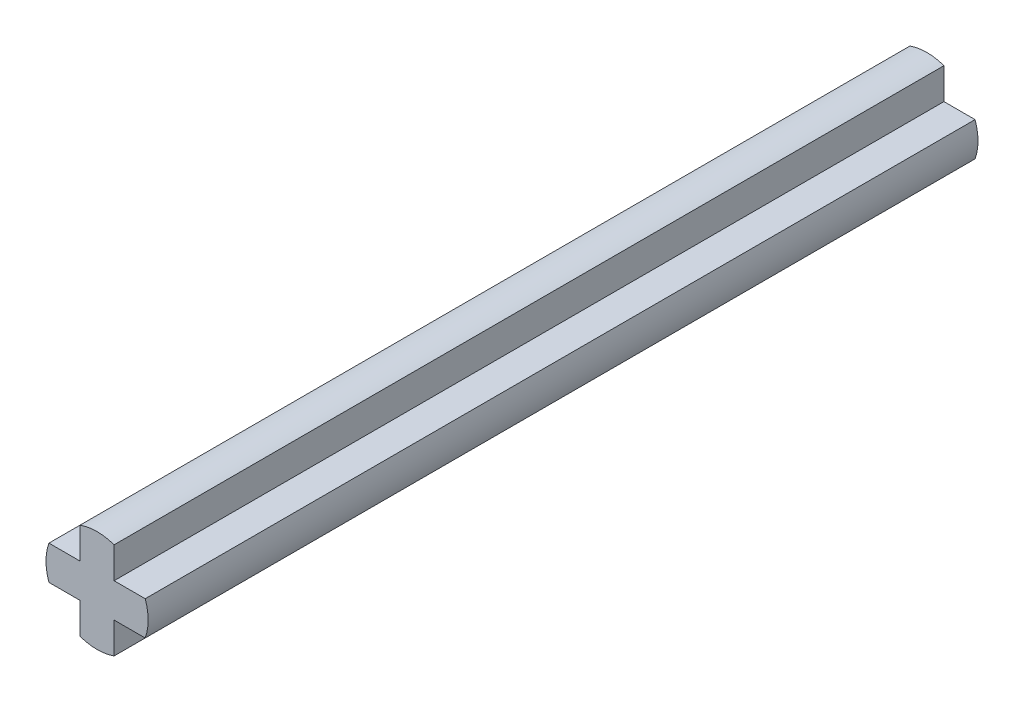
SolidWorks part; units mm, degrees
ref_plane "Plan de face" through (0, 0, 0) normal (0, 0, 1) x (1, 0, 0)
ref_plane "Plan de dessus" through (0, 0, 0) normal (0, 1, 0) x (1, 0, 0)
ref_plane "Plan de droite" through (0, 0, 0) normal (1, 0, 0) x (0, 0, -1)
sketch "Esquisse1" plane through (0, 0, 0) normal (0, 0, 1) x (1, 0, 0)
  line L0 (0.8, 0.8) -> (2.2627, 0.8)
  line L1 (-0.8, -0.8) -> (-0.8, -2.2627)
  line L2 (-0.8, 2.2627) -> (-0.8, 0.8)
  line L3 (0.8, -0.8) -> (2.2627, -0.8)
  line L4 (0.8, 2.2627) -> (0.8, 0.8)
  line L5 (-2.2627, 0.8) -> (-0.8, 0.8)
  line L6 (0.8, -0.8) -> (0.8, -2.2627)
  line L7 (-2.2627, -0.8) -> (-0.8, -0.8)
  arc A0 (0.8, 2.2627) -> (-0.8, 2.2627) centre (0, 0) ccw
  arc A1 (-2.2627, 0.8) -> (-2.2627, -0.8) centre (0, 0) ccw
  arc A2 (-0.8, -2.2627) -> (0.8, -2.2627) centre (0, 0) ccw
  arc A3 (2.2627, -0.8) -> (2.2627, 0.8) centre (0, 0) ccw
  dimension "D1" = 4.8
  dimension "D3" = 0.8
  dimension "D4" = 0.8
extrude "Boss.-Extru.1" add sketch "Esquisse1" along normal blind 39
